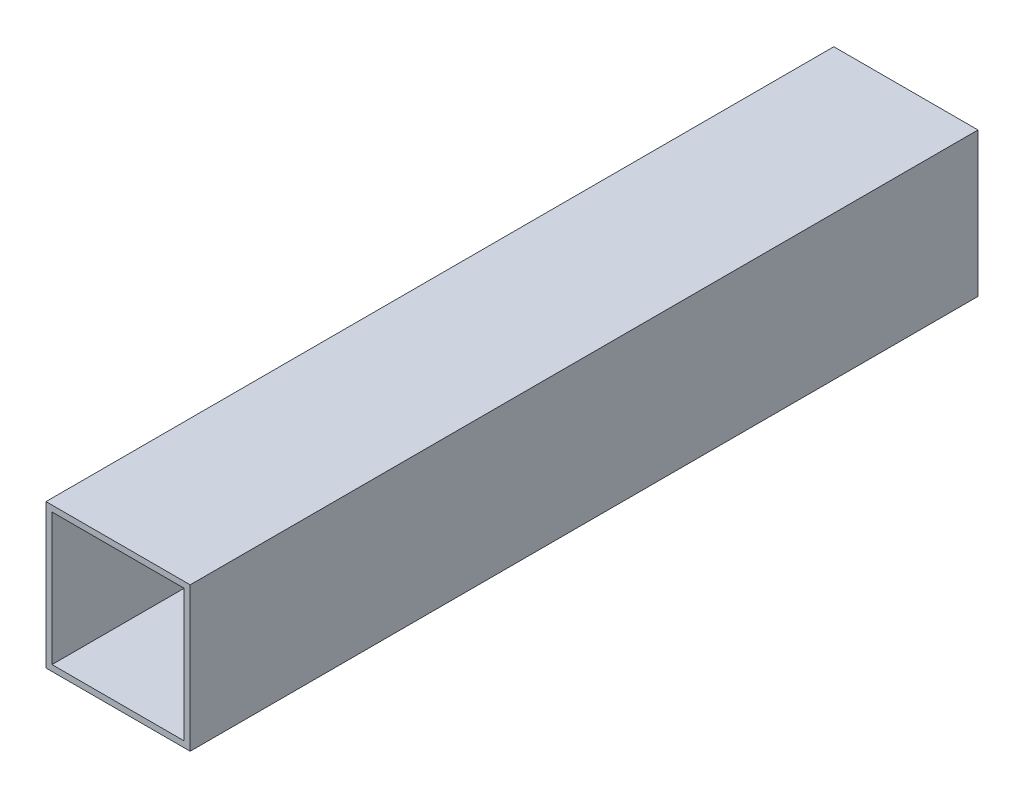
SolidWorks part; units mm, degrees
ref_plane "Front Plane" through (0, 0, 0) normal (0, 0, 1) x (1, 0, 0)
ref_plane "Top Plane" through (0, 0, 0) normal (0, 1, 0) x (1, 0, 0)
ref_plane "Right Plane" through (0, 0, 0) normal (1, 0, 0) x (0, 0, -1)
sketch "Sketch1" plane through (0, 0, 0) normal (0, 0, 1) x (1, 0, 0)
  line L0 (-34.925, 34.925) -> (34.925, 34.925)
  line L1 (-38.1, -38.1) -> (38.1, -38.1)
  line L2 (-38.1, -38.1) -> (-38.1, 38.1)
  line L3 (-38.1, 38.1) -> (38.1, 38.1)
  line L4 (38.1, -38.1) -> (38.1, 38.1)
  line L5 (-38.1, -38.1) -> (38.1, 38.1) construction
  line L6 (-38.1, 38.1) -> (38.1, -38.1) construction
  line L7 (34.925, -34.925) -> (34.925, 34.925)
  line L8 (-34.925, -34.925) -> (34.925, -34.925)
  line L9 (-34.925, -34.925) -> (-34.925, 34.925)
  point P0 (0, 0)
  dimension "D1" = 76.2
  dimension "D2" = 3.175
extrude "Boss-Extrude1" add sketch "Sketch1" along normal mid plane 416.4
